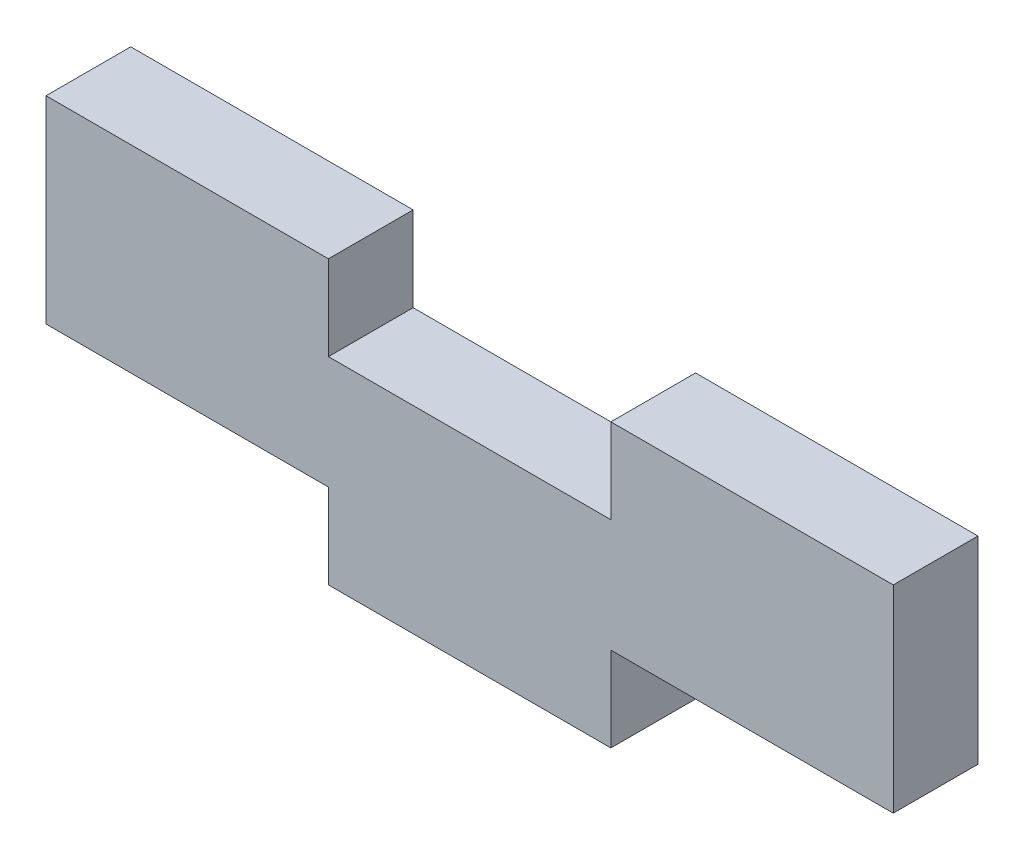
SolidWorks part; units mm, degrees
ref_plane "Front Plane" through (0, 0, 0) normal (0, 0, 1) x (1, 0, 0)
ref_plane "Top Plane" through (0, 0, 0) normal (0, 1, 0) x (1, 0, 0)
ref_plane "Right Plane" through (0, 0, 0) normal (1, 0, 0) x (0, 0, -1)
sketch "Sketch1" plane through (0, 0, 0) normal (0, 0, 1) x (1, 0, 0)
  line L0 (0, 0) -> (-10, 0)
  line L1 (-10, 0) -> (-10, -3)
  line L2 (-10, -3) -> (-20, -3)
  line L3 (-20, -3) -> (-20, 0)
  line L4 (-20, 0) -> (-30, 0)
  line L5 (-30, 0) -> (-30, 7)
  line L6 (-30, 7) -> (-20, 7)
  line L7 (-20, 7) -> (-20, 4)
  line L8 (-20, 4) -> (-10, 4)
  line L9 (-10, 4) -> (-10, 7)
  line L10 (-10, 7) -> (0, 7)
  line L11 (0, 7) -> (0, 0)
  dimension "D1" = 10
  dimension "D2" = 10
  dimension "D3" = 10
  dimension "D4" = 7
  dimension "D5" = 10
  dimension "D6" = 10
  dimension "D7" = 3
  dimension "D8" = 3
  dimension "D9" = 3
extrude "Boss-Extrude1" add sketch "Sketch1" along normal blind 3
